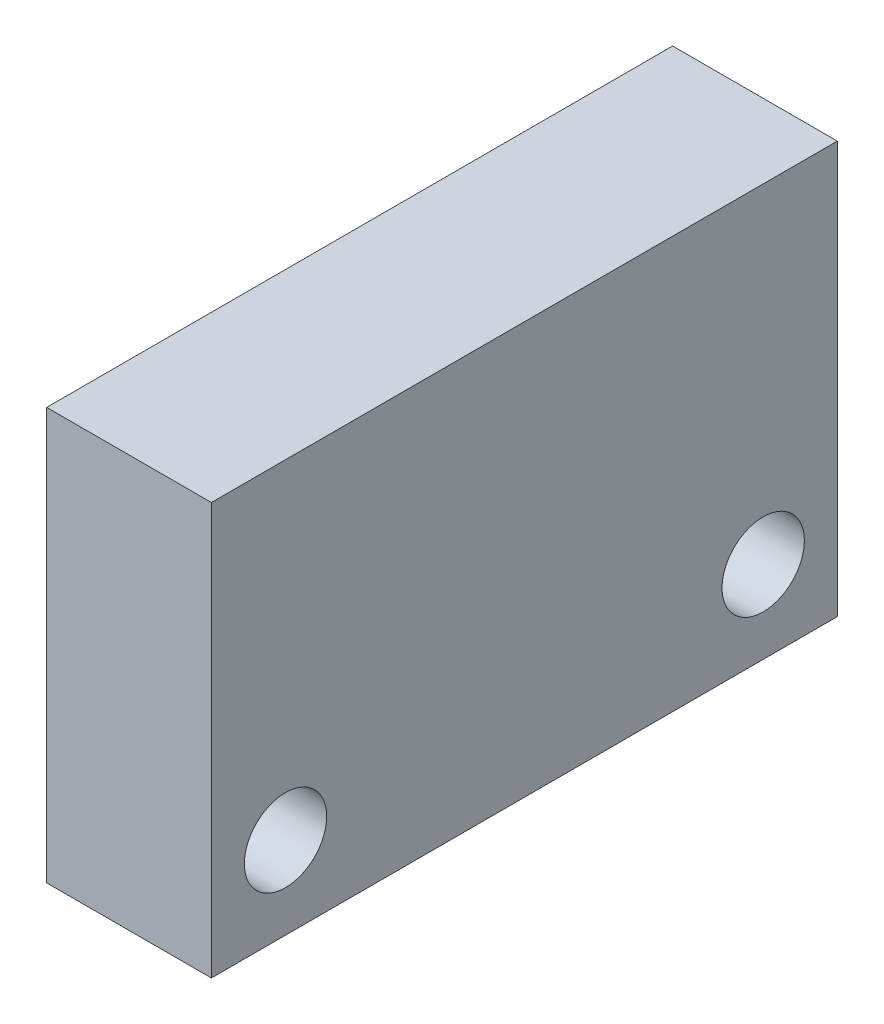
SolidWorks part; units mm, degrees
ref_plane "Front Plane" through (0, 0, 0) normal (0, 0, 1) x (1, 0, 0)
ref_plane "Top Plane" through (0, 0, 0) normal (0, 1, 0) x (1, 0, 0)
ref_plane "Right Plane" through (0, 0, 0) normal (1, 0, 0) x (0, 0, -1)
sketch "Sketch1" plane through (0, 0, 0) normal (0, 1, 0) x (1, 0, 0)
  line L1 (10, 38) -> (-10, 38)
  line L2 (10, 38) -> (10, -38)
  line L3 (10, -38) -> (-10, -38)
  line L4 (-10, 38) -> (-10, -38)
  line L5 (10, 38) -> (-10, -38) construction
  line L6 (10, -38) -> (-10, 38) construction
  point P0 (0, 0)
  dimension "D1" = 76
  dimension "D2" = 20
extrude "Boss-Extrude1" add sketch "Sketch1" along normal blind 50
sketch "Sketch2" plane through (10, 0, 0) normal (1, 0, 0) x (0, 0, -1)
  line L0 (0, 41.4355) -> (0, -2.1038) construction
  line L1 (-38, 0) -> (38, 0) construction
  circle A0 centre (-29, 10) radius 5
  circle A1 centre (29, 10) radius 5
  dimension "D1" = 10
  dimension "D2" = 10
  dimension "D3" = 58
extrude "Cut-Extrude2" cut sketch "Sketch2" against normal through all contours A0 | A1
